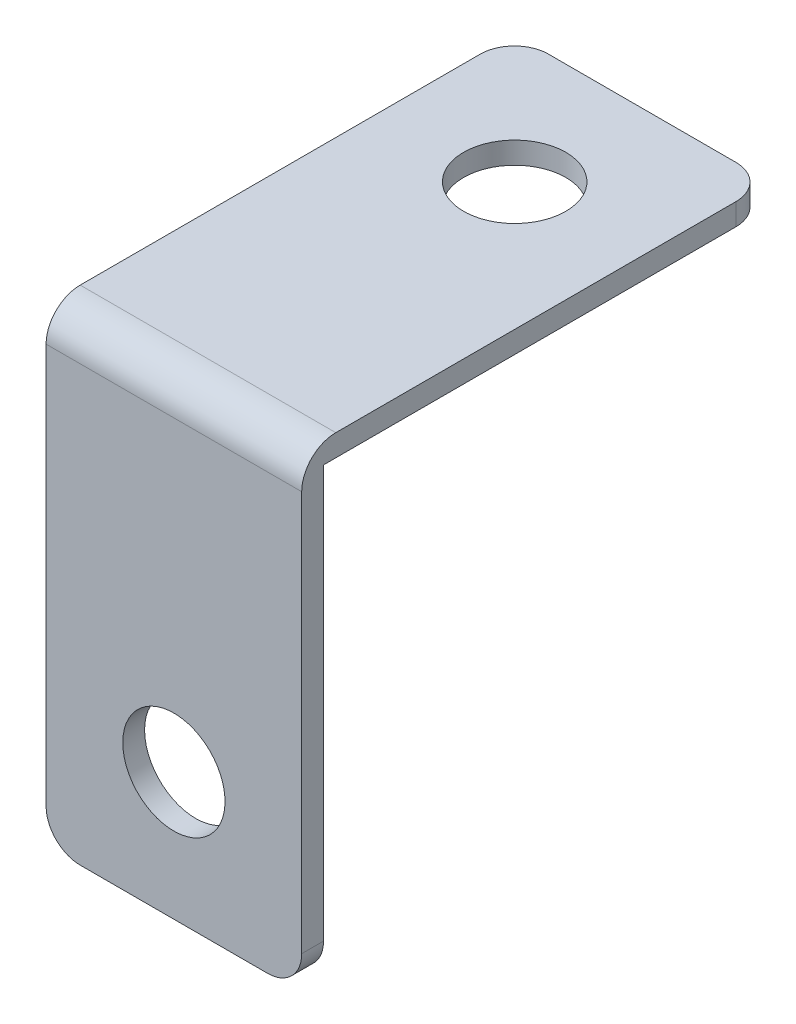
SolidWorks part; units mm, degrees
ref_plane "Front Plane" through (0, 0, 0) normal (0, 0, 1) x (1, 0, 0)
ref_plane "Top Plane" through (0, 0, 0) normal (0, 1, 0) x (1, 0, 0)
ref_plane "Right Plane" through (0, 0, 0) normal (1, 0, 0) x (0, 0, -1)
sketch "Sketch1" plane through (0, 0, 0) normal (0, 0, 1) x (1, 0, 0)
  line L1 (0, 0) -> (9.525, 0)
  line L2 (0, 0) -> (0, 0.8128)
  line L3 (0, 0.8128) -> (9.525, 0.8128)
  line L4 (9.525, 0) -> (9.525, 0.8128)
  dimension "D1" = 0.8128
  dimension "D2" = 9.525
extrude "Boss-Extrude1" add sketch "Sketch1" along normal blind 17.4498
sketch "Sketch2" plane through (0, 0.8128, 0) normal (0, 1, 0) x (1, 0, 0)
  line L0 (9.525, -17.4498) -> (9.525, 0) construction
  line L1 (0, -17.4498) -> (9.525, -17.4498)
  line L2 (0, -17.4498) -> (0, -16.637)
  line L3 (0, -16.637) -> (9.525, -16.637)
  line L4 (9.525, -17.4498) -> (9.525, -16.637)
  dimension "D1" = 0.8128
extrude "Boss-Extrude2" add sketch "Sketch2" against normal blind 17.4498
sketch "Sketch3" plane through (0, 0, 0) normal (0, -1, 0) x (1, 0, 0)
  line L0 (9.525, 16.637) -> (9.525, 0) construction
  line L1 (0, 17.4498) -> (9.525, 17.4498) construction
  circle A0 centre (4.7625, 4.7498) radius 1.905
  dimension "D1" = 3.81
  dimension "D2" = 4.7625
  dimension "D3" = 12.7
extrude "Cut-Extrude1" cut sketch "Sketch3" against normal blind 17.4498
sketch "Sketch4" plane through (0, 0, 16.637) normal (0, 0, -1) x (-1, 0, 0)
  line L0 (-9.525, -16.637) -> (-9.525, 0) construction
  line L1 (-9.525, 0.8128) -> (0, 0.8128) construction
  circle A0 centre (-4.7625, -11.8872) radius 1.905
  dimension "D1" = 3.81
  dimension "D2" = 4.7625
  dimension "D3" = 12.7
extrude "Cut-Extrude2" cut sketch "Sketch4" against normal blind 17.4498
fillet "Fillet1" radius 1.27 5 edges at (4.7625, 0.8128, 17.4498) (0, -16.637, 17.0434) (9.525, -16.637, 17.0434) (9.525, 0.4064, 0) (0, 0.4064, 0)
